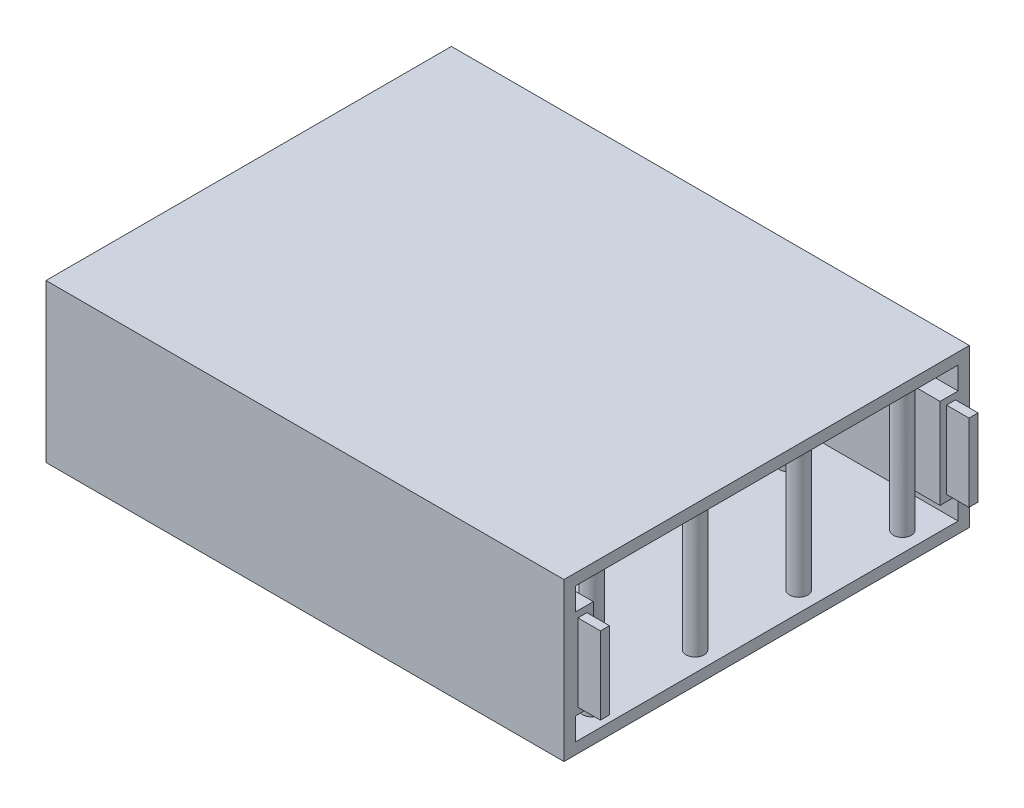
SolidWorks part; units mm, degrees
ref_plane "Спереди" through (0, 0, 0) normal (0, 0, 1) x (1, 0, 0)
ref_plane "Сверху" through (0, 0, 0) normal (0, 1, 0) x (1, 0, 0)
ref_plane "Справа" through (0, 0, 0) normal (1, 0, 0) x (0, 0, -1)
sketch "Эскиз1" plane through (0, 0, 0) normal (0, 1, 0) x (1, 0, 0)
  line L1 (-57.5, -45) -> (57.5, -45)
  line L2 (-57.5, -45) -> (-57.5, 45)
  line L3 (-57.5, 45) -> (57.5, 45)
  line L4 (57.5, -45) -> (57.5, 45)
  line L5 (-57.5, -45) -> (57.5, 45) construction
  line L6 (-57.5, 45) -> (57.5, -45) construction
  point P0 (0, 0)
extrude "Бобышка-Вытянуть1" add sketch "Эскиз1" along normal blind 35
sketch "Эскиз2" plane through (57.5, 0, 0) normal (1, 0, 0) x (0, 0, -1)
  line L0 (0, -1000) -> (0, 49000) construction
  line L1 (-45, 0) -> (45, 0) construction
  line L2 (-1045, 17.5) -> (48955, 17.5) construction
  line L3 (-45, 35) -> (-45, 0) construction
  line L5 (-42.5, 2.5) -> (42.5, 2.5)
  line L6 (-42.5, 2.5) -> (-42.5, 32.5)
  line L7 (-42.5, 32.5) -> (42.5, 32.5)
  line L8 (42.5, 2.5) -> (42.5, 32.5)
  line L9 (-42.5, 2.5) -> (42.5, 32.5) construction
  line L10 (-42.5, 32.5) -> (42.5, 2.5) construction
  point P5 (0, 0)
  point P6 (0, 17.5)
  point P10 (-45, 17.5)
extrude "Вырез-Вытянуть1" cut sketch "Эскиз2" against normal through all
sketch "Эскиз3" plane through (57.5, 0, 0) normal (1, 0, 0) x (0, 0, -1)
  line L0 (38.5, 27.5) -> (42.5, 27.5)
  line L1 (-42.5, 32.5) -> (-42.5, 2.5) construction
  line L2 (42.5, 27.5) -> (42.5, 7.5)
  line L3 (-42.5, 7.5) -> (-42.5, 27.5)
  line L4 (-42.5, 27.5) -> (-38.5, 27.5)
  line L5 (-38.5, 27.5) -> (-38.5, 7.5)
  line L6 (-38.5, 7.5) -> (-42.5, 7.5)
  line L7 (42.5, 7.5) -> (38.5, 7.5)
  line L8 (38.5, 7.5) -> (38.5, 27.5)
  dimension "D1" = 2
extrude "Бобышка-Вытянуть2" add sketch "Эскиз3" against normal blind 10
sketch "Эскиз4" plane through (57.5, 0, 0) normal (1, 0, 0) x (0, 0, -1)
  line L1 (39.9142, 26.0858) -> (39.9142, 8.9142)
  line L2 (-39.9142, 8.9142) -> (-39.9142, 26.0858)
  line L3 (-39.9142, 26.0858) -> (-41.9142, 26.0858)
  line L4 (-41.9142, 26.0858) -> (-41.9142, 8.9142)
  line L5 (-41.9142, 8.9142) -> (-39.9142, 8.9142)
  line L6 (39.9142, 8.9142) -> (41.9142, 8.9142)
  line L7 (41.9142, 8.9142) -> (41.9142, 26.0858)
  line L8 (41.9142, 26.0858) -> (39.9142, 26.0858)
extrude "Бобышка-Вытянуть3" add sketch "Эскиз4" along normal blind 5
sketch "Эскиз5" plane through (0, 2.5, 0) normal (0, 1, 0) x (1, 0, 0)
  circle A0 centre (-52.1136, 34.564) radius 2
  circle A1 centre (-52.1136, 11.564) radius 2
  circle A2 centre (-52.1136, -11.436) radius 2
  circle A3 centre (-52.1136, -34.436) radius 2
  circle A4 centre (53.0545, 34.564) radius 2
  circle A5 centre (53.0545, 11.564) radius 2
  circle A6 centre (53.0545, -11.436) radius 2
  circle A7 centre (53.0545, -34.436) radius 2
  circle A8 centre (-12.1136, 34.564) radius 2
  circle A9 centre (27.8864, 34.564) radius 2
  circle A10 centre (-12.1136, -34.436) radius 2
  circle A11 centre (27.8864, -34.436) radius 2
  circle A12 centre (0, 0) radius 10
  dimension "D1" = 4
  dimension "D2" = 4
  dimension "D3" = 3
  dimension "D4" = 3
extrude "Бобышка-Вытянуть4" add sketch "Эскиз5" along normal blind 32
